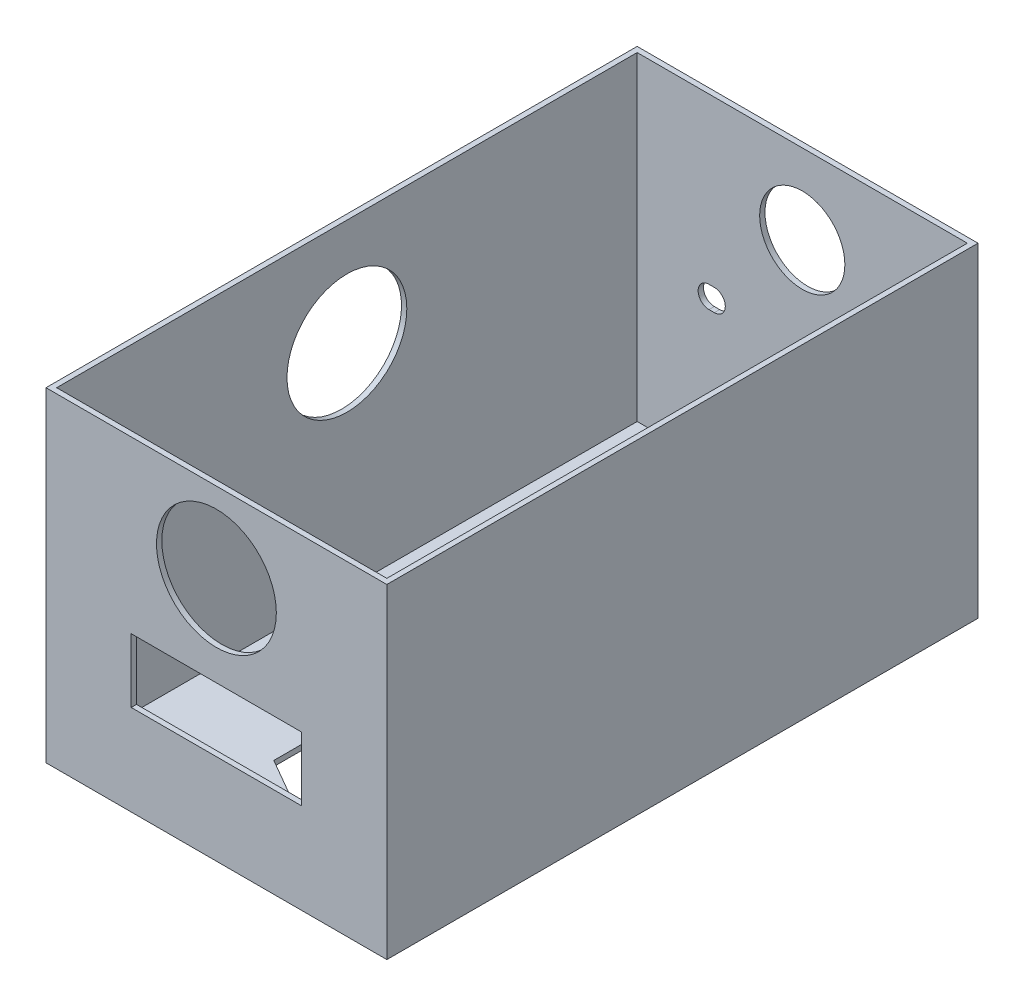
SolidWorks part; units mm, degrees
ref_plane "Ön Düzlem" through (0, 0, 0) normal (0, 0, 1) x (1, 0, 0)
ref_plane "Üst Düzlem" through (0, 0, 0) normal (0, 1, 0) x (1, 0, 0)
ref_plane "Sağ Düzlem" through (0, 0, 0) normal (1, 0, 0) x (0, 0, -1)
sketch "Çizim1" plane through (0, 0, 0) normal (0, 1, 0) x (1, 0, 0)
  line L1 (-30, 30) -> (30, 30)
  line L2 (-30, 30) -> (-30, -30)
  line L3 (-30, -30) -> (30, -30)
  line L4 (30, 30) -> (30, -30)
  line L5 (-30, 30) -> (30, -30) construction
  line L6 (-30, -30) -> (30, 30) construction
  point P1 (0, 0)
  dimension "D1" = 60
  dimension "D2" = 60
extrude "Yükseklik-Ekstrüzyon1" add sketch "Çizim1" along normal blind 1
sketch "Çizim2" plane through (0, 1, 0) normal (0, 1, 0) x (1, 0, 0)
  line L4 (-30, 30) -> (-30, -30) construction
  line L5 (-30, -30) -> (30, -30) construction
  line L7 (30, 30) -> (-30, 30) construction
  line L8 (30, -30) -> (30, 30) construction
  circle A0 centre (-10, -25) radius 1.6
  circle A2 centre (15, -25) radius 1.6
  circle A3 centre (-10, 27) radius 1.6
  circle A4 centre (15, 27) radius 1.6
  point P6 (7.6117, -44.74)
  point P7 (-8, -27)
  point P10 (18.7487, -25)
  point P11 (15, -25)
  point P12 (15, -25)
  point P15 (-10, 17.7914)
  point P16 (0, 0)
  point P18 (-10.7834, 27.1479)
  point P22 (15, 27)
  dimension "D5" = 3.2
  dimension "D6" = 3.2
  dimension "D9" = 3.2
  dimension "D11" = 3.2
  dimension "D1" = 20
  dimension "D2" = 5
  dimension "D3" = 5
  dimension "D4" = 25
  dimension "D7" = 52
  dimension "D8" = 3
  dimension "D10" = 3
  dimension "D12" = 15
extrude "Yükseklik-Ekstrüzyon2" add sketch "Çizim2" along normal blind 7
sketch "Çizim3" plane through (30, 0, 0) normal (1, 0, 0) x (0, 0, -1)
  line L4 (-30, 0) -> (30, 0)
  line L5 (30, 0) -> (30, 1)
  line L6 (30, 1) -> (-30, 1)
  line L7 (-30, 1) -> (-30, 0)
  line L8 (-30, 0) -> (30, 0)
  line L9 (30, 0) -> (30, 1)
  line L10 (30, 1) -> (-30, 1)
  line L11 (-30, 1) -> (-30, 0)
  dimension "D1" = 0
extrude "Yükseklik-Ekstrüzyon3" add sketch "Çizim3" along normal blind 2
mirror "Aynalama1" about plane through (0, 0, 0) normal (1, 0, 0) of "Yükseklik-Ekstrüzyon3"
sketch "Çizim4" plane through (0, 0, 30) normal (0, 0, 1) x (1, 0, 0)
  line L0 (-32, 0) -> (32, 0) construction
  line L1 (-19.5, 1) -> (19.5, 1)
  line L2 (-19.5, 1) -> (-19.5, 0)
  line L3 (-19.5, 0) -> (19.5, 0)
  line L4 (19.5, 1) -> (19.5, 0)
  line L5 (-19.5, 1) -> (19.5, 0) construction
  line L6 (-19.5, 0) -> (19.5, 1) construction
  line L7 (-32, 1) -> (32, 1) construction
  point P0 (0, 0.5)
  point P7 (0, 0)
  point P9 (-19.5, 1.158)
  dimension "D1" = 39
extrude "Yükseklik-Ekstrüzyon4" add sketch "Çizim4" along normal blind 51
sketch "Çizim5" plane through (0, 1, 0) normal (0, 1, 0) x (1, 0, 0)
  line L0 (-32, -30) -> (-19.5, -30) construction
  line L1 (-19.5, -81) -> (-19.5, -30) construction
  line L2 (0, -0.55) -> (0, 0.55) construction
  line L3 (19.5, -81) -> (-19.5, -81) construction
  circle A0 centre (-16.5, -32) radius 1.6
  circle A1 centre (16.5, -32) radius 1.6
  circle A2 centre (-16.5, -78) radius 1.6
  circle A3 centre (16.5, -78) radius 1.6
  point P12 (-17.5, -77.7833)
  point P13 (-17.5, -78)
  dimension "D1" = 3.2
  dimension "D5" = 3.2
  dimension "D2" = 2
  dimension "D3" = 3
  dimension "D4" = 46
  dimension "D6" = 3
extrude "Yükseklik-Ekstrüzyon5" add sketch "Çizim5" along normal blind 5
sketch "Çizim6" plane through (19.5, 0, 0) normal (1, 0, 0) x (0, 0, -1)
  line L4 (-30, 0) -> (-30, 1)
  line L5 (-30, 1) -> (-81, 1)
  line L6 (-81, 1) -> (-81, 0)
  line L7 (-81, 0) -> (-30, 0)
  line L8 (-30, 0) -> (-30, 1)
  line L9 (-30, 1) -> (-81, 1)
  line L10 (-81, 1) -> (-81, 0)
  line L11 (-81, 0) -> (-30, 0)
  dimension "D1" = 0
extrude "Yükseklik-Ekstrüzyon6" add sketch "Çizim6" along normal up to surface (12.5 mm away) up to face at (32, 0.5, 0)
sketch "Çizim7" plane through (-19.5, 0, 0) normal (-1, 0, 0) x (0, 0, 1)
  line L4 (30, 1) -> (30, 0)
  line L5 (30, 0) -> (81, 0)
  line L6 (81, 0) -> (81, 1)
  line L7 (81, 1) -> (30, 1)
  line L8 (30, 1) -> (30, 0)
  line L9 (30, 0) -> (81, 0)
  line L10 (81, 0) -> (81, 1)
  line L11 (81, 1) -> (30, 1)
  dimension "D1" = 0
extrude "Yükseklik-Ekstrüzyon7" add sketch "Çizim7" along normal up to surface (12.5 mm away) up to face at (-32, 0.5, 0)
sketch "Çizim8" plane through (0, 1, 0) normal (0, 1, 0) x (1, 0, 0)
  line L0 (32, -81) -> (-32, -81) construction
  line L1 (-10, -5.7735) -> (0, -11.547)
  line L2 (0, -11.547) -> (10, -5.7735)
  line L3 (10, -5.7735) -> (10, 5.7735)
  line L4 (10, 5.7735) -> (0, 11.547)
  line L5 (0, 11.547) -> (-10, 5.7735)
  line L6 (-10, 5.7735) -> (-10, -5.7735)
  line L7 (-10, -60.2265) -> (0, -66)
  line L8 (0, -66) -> (10, -60.2265)
  line L9 (10, -60.2265) -> (10, -48.6795)
  line L10 (10, -48.6795) -> (0, -42.906)
  line L11 (0, -42.906) -> (-10, -48.6795)
  line L12 (-10, -48.6795) -> (-10, -60.2265)
  circle A0 centre (0, 0) radius 10 construction
  point P1 (5, -8.6603)
  point P17 (0, 0)
  dimension "D1" = 20
  dimension "D2" = 20
  dimension "D3" = 20
  dimension "D4" = 20
  dimension "D5" = 15
extrude "Kes-Ekstrüzyon1" cut sketch "Çizim8" against normal through all
sketch "Çizim9" plane through (0, 1, 0) normal (0, 1, 0) x (1, 0, 0)
  line L0 (-31, -80) -> (31, -80)
  line L1 (31, -80) -> (31, 29)
  line L2 (31, 29) -> (-31, 29)
  line L3 (-31, 29) -> (-31, -80)
  line L4 (-32, -81) -> (32, -81)
  line L5 (32, -81) -> (32, 30)
  line L6 (32, 30) -> (-32, 30)
  line L7 (-32, 30) -> (-32, -81)
  line L8 (-32, -81) -> (32, -81)
  line L9 (32, -81) -> (32, 30)
  line L10 (32, 30) -> (-32, 30)
  line L11 (-32, 30) -> (-32, -81)
  dimension "D1" = 0
  dimension "D2" = 1
extrude "Yükseklik-Ekstrüzyon8" add sketch "Çizim9" along normal blind 60 contours L0 L1 L2 L3
sketch "Çizim10" plane through (0, 0, 81) normal (0, 0, 1) x (1, 0, 0)
  line L0 (-32, 0) -> (32, 0) construction
  line L1 (-16, 29) -> (16, 29)
  line L2 (-16, 29) -> (-16, 17)
  line L3 (-16, 17) -> (16, 17)
  line L4 (16, 29) -> (16, 17)
  line L5 (-32, 61) -> (32, 61) construction
  circle A0 centre (0, 46) radius 11.25
  point P4 (0, 17)
  point P8 (0, 46.8504)
  point P11 (0, 0)
  point P13 (0, 45.2652)
  point P14 (0, 0)
  dimension "D3" = 22.5
  dimension "D1" = 12
  dimension "D2" = 32
  dimension "D4" = 17
  dimension "D5" = 15
extrude "Kes-Ekstrüzyon2" cut sketch "Çizim10" against normal up to next
sketch "Çizim11" plane through (-32, 0, 0) normal (-1, 0, 0) x (0, 0, 1)
  line L0 (81, 0) -> (-30, 0) construction
  line L1 (-30, 61) -> (81, 61) construction
  circle A0 centre (25.5, 41) radius 11.25
  point P2 (0, 0)
  point P5 (25.5, 0)
  dimension "D1" = 22.5
  dimension "D2" = 20
extrude "Kes-Ekstrüzyon3" cut sketch "Çizim11" against normal up to next
sketch "Çizim12" plane through (0, 0, -30) normal (0, 0, -1) x (-1, 0, 0)
  line L0 (-32, 61) -> (32, 61) construction
  line L1 (-32, 0) -> (-32, 61) construction
  line L2 (-32, 0) -> (32, 0) construction
  line L3 (16.5, 28) -> (17.5, 28) construction
  line L4 (16.5, 30.05) -> (17.5, 30.05)
  line L5 (16.5, 25.95) -> (17.5, 25.95)
  line L6 (32, 0) -> (32, 61) construction
  circle A0 centre (0, 46) radius 8
  circle A1 centre (-17, 28) radius 2.55
  arc A3 (16.5, 30.05) -> (16.5, 25.95) centre (16.5, 28) ccw
  arc A4 (17.5, 25.95) -> (17.5, 30.05) centre (17.5, 28) ccw
  point P13 (17, 28)
  point P18 (19.55, 28)
  point P19 (14.45, 28)
  point P20 (0, 0)
  dimension "D1" = 16
  dimension "D3" = 5.1
  dimension "D2" = 15
  dimension "D4" = 15
  dimension "D5" = 28
  dimension "D6" = 5.1
  dimension "D7" = 4.1
  dimension "D8" = 15
extrude "Kes-Ekstrüzyon4" cut sketch "Çizim12" against normal up to next
sketch "Çizim14" plane through (0, 0, -30) normal (0, 0, -1) x (-1, 0, 0)
  line L0 (-32, 0) -> (-32, 61) construction
  line L1 (-31, 16.4) -> (-22, 16.4)
  line L2 (-31, 16.4) -> (-31, 5)
  line L3 (-31, 5) -> (-22, 5)
  line L4 (-22, 16.4) -> (-22, 5)
  line L5 (-32, 0) -> (32, 0) construction
  line L6 (-2.25, 17.5) -> (2.25, 17.5) construction
  line L7 (-2.25, 19.5) -> (2.25, 19.5)
  line L8 (-2.25, 15.5) -> (2.25, 15.5)
  arc A0 (-2.25, 19.5) -> (-2.25, 15.5) centre (-2.25, 17.5) ccw
  arc A1 (2.25, 15.5) -> (2.25, 19.5) centre (2.25, 17.5) ccw
  point P10 (0, 17.5)
  point P15 (0, 0)
  point P16 (-4.25, 17.5)
  point P19 (4.25, 17.5)
  dimension "D1" = 1
  dimension "D2" = 5
  dimension "D3" = 11.4
  dimension "D4" = 9
  dimension "D5" = 19.5
  dimension "D6" = 8.5
  dimension "D7" = 4
extrude "Kes-Ekstrüzyon5" cut sketch "Çizim14" against normal up to next
